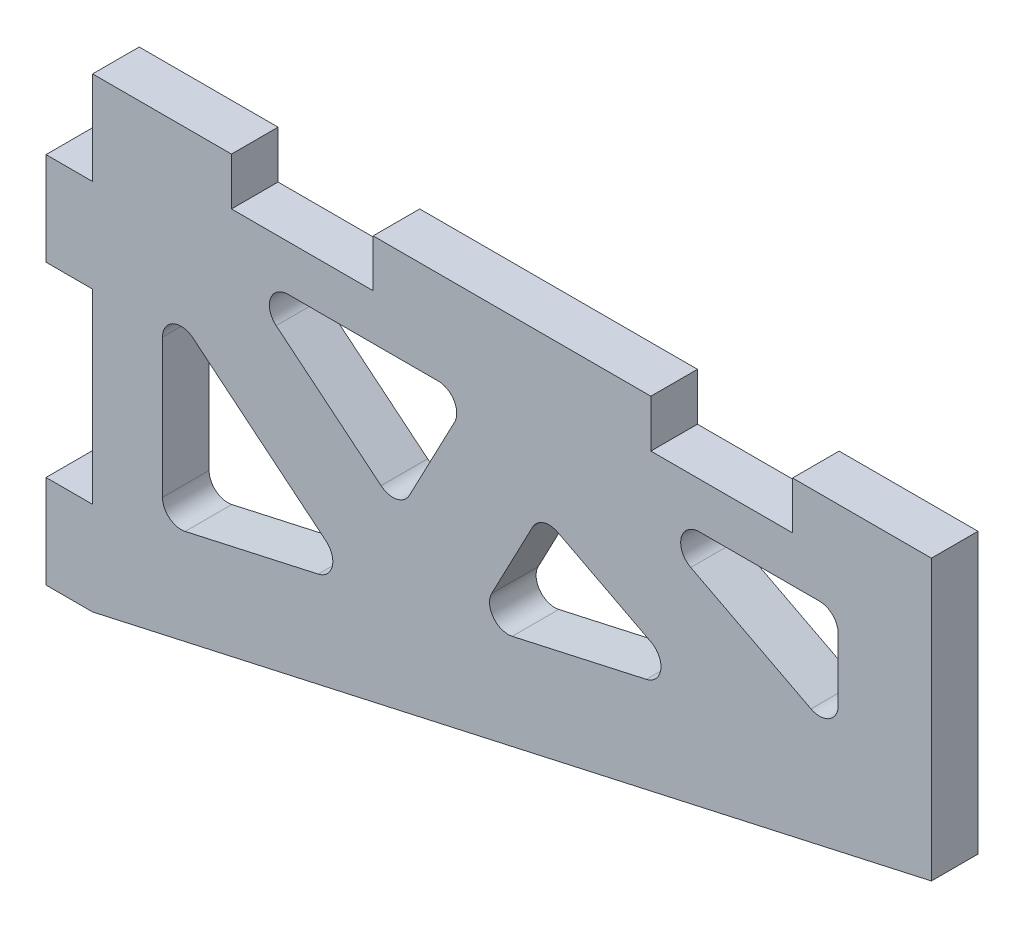
SolidWorks part; units mm, degrees
ref_plane "Front Plane" through (0, 0, 0) normal (0, 0, 1) x (1, 0, 0)
ref_plane "Top Plane" through (0, 0, 0) normal (0, 1, 0) x (1, 0, 0)
ref_plane "Right Plane" through (0, 0, 0) normal (1, 0, 0) x (0, 0, -1)
sketch "Sketch2" plane through (0, 0, 0) normal (0, 0, 1) x (1, 0, 0)
  line L0 (0, -127) -> (27.7435, -127)
  line L5 (0, -69.85) -> (40.1279, -69.85) construction
  line L6 (0, -127) -> (0, -69.85) construction
  line L7 (0, -63.5) -> (45.8652, -63.5) construction
  line L8 (0, -63.5) -> (114.3, -38.1)
  line L9 (114.3, -38.1) -> (114.3, 0)
  line L11 (0, 0) -> (0, -12.7) construction
  line L12 (19.05, 0) -> (19.05, -6.35) construction
  line L13 (0, -63.5) -> (0, -25.4) construction
  line L16 (-6.35, -63.5) -> (0, -63.5)
  line L18 (0, 0) -> (19.05, 0)
  line L20 (-6.35, -12.7) -> (0, -12.7)
  line L21 (0, -25.4) -> (0, -50.8)
  line L22 (0, -50.8) -> (-6.35, -50.8)
  line L23 (-6.35, -50.8) -> (-6.35, -63.5)
  line L24 (0, 0) -> (0, -12.7)
  line L25 (-6.35, -12.7) -> (-6.35, -25.4)
  line L26 (-6.35, -25.4) -> (0, -25.4)
  line L27 (0, -25.4) -> (0, -63.5) construction
  line L28 (0, -12.7) -> (0, 0) construction
  line L29 (-6.35, -63.5) -> (-6.35, 0) construction
  line L30 (19.05, -6.35) -> (38.1, -6.35) construction
  line L31 (38.1, -6.35) -> (38.1, 0) construction
  line L32 (18.923, 0) -> (18.923, -6.477)
  line L33 (18.923, -6.477) -> (38.227, -6.477)
  line L34 (38.227, -6.477) -> (38.227, 0)
  line L35 (57.15, 0) -> (57.15, -20.9685) construction
  line L36 (76.073, -6.477) -> (76.073, 0)
  line L37 (95.377, -6.477) -> (76.073, -6.477)
  line L38 (95.377, 0) -> (95.377, -6.477)
  line L39 (76.2, -6.35) -> (76.2, 0) construction
  line L40 (95.25, -6.35) -> (76.2, -6.35) construction
  line L41 (95.25, 0) -> (95.25, -6.35) construction
  line L42 (38.1, 0) -> (76.2, 0)
  line L43 (95.25, 0) -> (114.3, 0)
  point P21 (-6.35, -31.75)
  dimension "D1" = 57.15
  dimension "D2" = 6.35
  dimension "D3" = 114.3
  dimension "D4" = 12.7
  dimension "D5" = 12.7
  dimension "D6" = 6.35
  dimension "D7" = 38.1
  dimension "D8" = 12.7
  dimension "D9" = 6.35
  dimension "D10" = 19.05
  dimension "D11" = 19.05
  dimension "D13" = 19.05
  dimension "D12" = 0.127
extrude "Boss-Extrude1" add sketch "Sketch2" against normal blind 6.35
sketch "Sketch3" plane through (0, 0, 0) normal (0, 0, 1) x (1, 0, 0)
  line L0 (9.525, -12.7) -> (9.525, -48.3735)
  line L1 (9.525, -48.3735) -> (101.6, -27.9124)
  line L2 (101.6, -27.9124) -> (101.6, -12.7)
  line L3 (101.6, -12.7) -> (9.525, -12.7)
  line L4 (0, 0) -> (18.923, 0) construction
  line L5 (114.3, -38.1) -> (114.3, 0) construction
  line L6 (0, -63.5) -> (114.3, -38.1) construction
  line L7 (0, -25.4) -> (0, -50.8) construction
  line L8 (9.525, -12.7) -> (43.7122, -40.7764) construction
  line L9 (13.5551, -7.7928) -> (47.7422, -35.8692)
  line L10 (5.4949, -17.6072) -> (39.6821, -45.6836)
  line L11 (43.7122, -40.7764) -> (58.4566, -12.7) construction
  line L12 (38.0902, -37.824) -> (52.8347, -9.7476)
  line L13 (49.3341, -43.7288) -> (64.0785, -15.6524)
  line L14 (58.4566, -12.7) -> (98.6776, -33.55) construction
  line L17 (61.379, -7.0625) -> (101.6, -27.9124)
  line L18 (55.5342, -18.3375) -> (95.7552, -39.1875)
  arc A0 (13.5551, -7.7928) -> (5.4949, -17.6072) centre (9.525, -12.7) ccw
  arc A1 (39.6821, -45.6836) -> (47.7422, -35.8692) centre (43.7122, -40.7764) ccw
  arc A2 (38.0902, -37.824) -> (49.3341, -43.7288) centre (43.7122, -40.7764) ccw
  arc A3 (64.0785, -15.6524) -> (52.8347, -9.7476) centre (58.4566, -12.7) ccw
  arc A6 (61.379, -7.0625) -> (55.5342, -18.3375) centre (58.4566, -12.7) ccw
  arc A7 (95.7552, -39.1875) -> (101.6, -27.9124) centre (98.6776, -33.55) ccw
  point P4 (26.6186, -26.7382)
  point P18 (51.0844, -26.7382)
  point P27 (78.5671, -23.125)
  point P32 (97.1064, -37.824)
  point P33 (0, 0)
  dimension "D5" = 6.35
  dimension "D1" = 12.7
  dimension "D2" = 12.7
  dimension "D3" = 12.7
  dimension "D4" = 9.525
extrude "Cut-Extrude1" cut sketch "Sketch3" against normal blind 6.35 contours L10 L0 L1 | L9 L12 L3 | L18 L13 L1 | L3 L17 L2
fillet "Fillet1" radius 2.54 12 edges at (82.2848, -32.2047, -3.175) (51.8321, -38.9719, -3.175) (61.1418, -21.2445, -3.175) (101.6, -27.9124, -3.175) (72.2542, -12.7, -3.175) (101.6, -12.7, -3.175) (35.8376, -42.5263, -3.175) (9.525, -20.917, -3.175) (51.2842, -12.7, -3.175) (41.7159, -30.92, -3.175) (19.5304, -12.7, -3.175) (9.525, -48.3735, -3.175)
